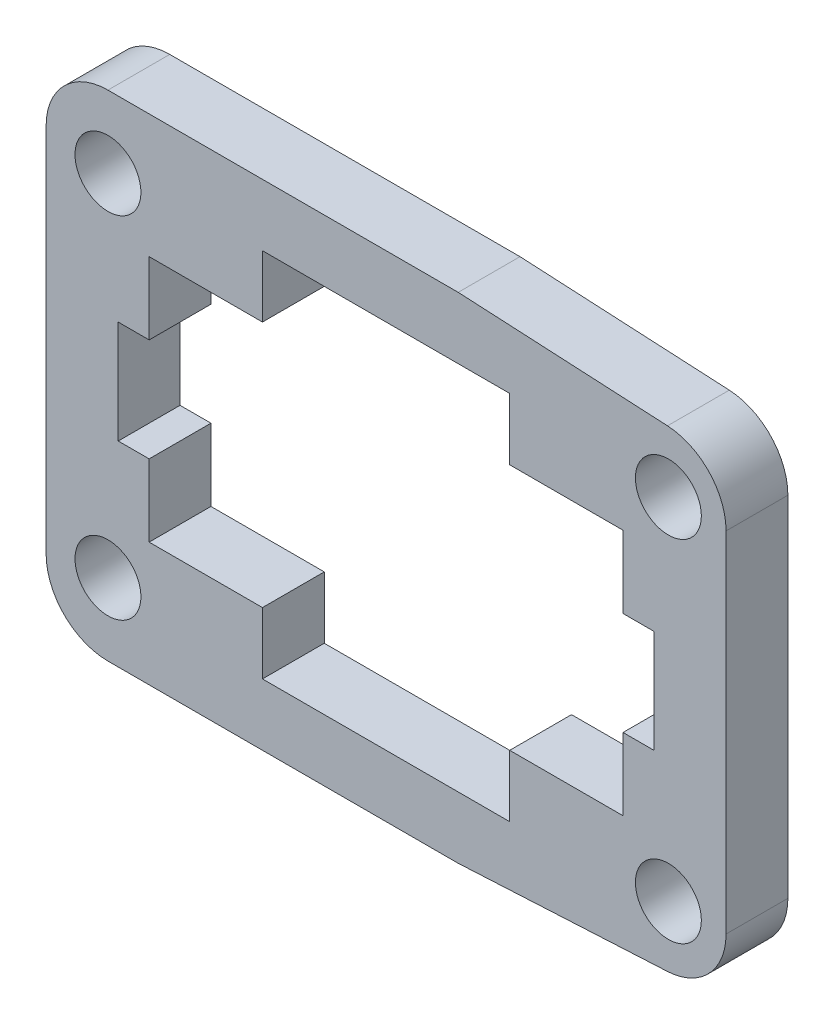
SolidWorks part; units mm, degrees
ref_plane "前视基准面" through (0, 0, 0) normal (0, 0, 1) x (1, 0, 0)
ref_plane "上视基准面" through (0, 0, 0) normal (0, 1, 0) x (1, 0, 0)
ref_plane "右视基准面" through (0, 0, 0) normal (1, 0, 0) x (0, 0, -1)
ref_plane "基准面4" through (0, 0, 3) normal (0, 0, 1) x (1, 0, 0)
sketch "草图1" plane through (0, 0, 3) normal (0, 0, 1) x (1, 0, 0)
  line L0 (13.8437, 23.9998) -> (-3.1571, 23.9998)
  line L1 (-6.1571, 20.9998) -> (-6.1571, 3)
  line L2 (-3.1571, 0) -> (13.8437, 0)
  line L3 (13.8437, 0) -> (24.0014, 0.533)
  line L4 (26.8442, 3.5289) -> (26.8442, 20.4719)
  line L5 (24.0011, 23.4678) -> (13.8437, 23.9998)
  line L6 (21.8432, 14.4995) -> (23.3435, 14.4995)
  line L7 (23.3435, 14.4995) -> (23.3435, 9.5)
  line L8 (23.3435, 9.5) -> (21.8432, 9.5)
  line L9 (21.8432, 9.5) -> (21.8432, 6)
  line L10 (21.8432, 6) -> (16.3434, 6)
  line L11 (16.3434, 6) -> (16.3434, 3)
  line L12 (16.3434, 3) -> (4.3434, 3)
  line L13 (4.3434, 3) -> (4.3434, 6)
  line L14 (4.3434, 6) -> (-1.1565, 6)
  line L15 (-1.1565, 6) -> (-1.1565, 9.5)
  line L16 (-1.1565, 9.5) -> (-2.6568, 9.5)
  line L17 (-2.6568, 9.5) -> (-2.6568, 14.4995)
  line L18 (-2.6568, 14.4995) -> (-1.1565, 14.4995)
  line L19 (-1.1565, 14.4995) -> (-1.1565, 17.9998)
  line L20 (-1.1565, 17.9998) -> (4.3434, 17.9998)
  line L21 (4.3434, 17.9998) -> (4.3434, 20.9998)
  line L22 (4.3434, 20.9998) -> (16.3434, 20.9998)
  line L23 (16.3434, 20.9998) -> (16.3434, 17.9998)
  line L24 (16.3434, 17.9998) -> (21.8432, 17.9998)
  line L25 (21.8432, 17.9998) -> (21.8432, 14.4995)
  arc A0 (-3.1571, 23.9998) -> (-6.1571, 20.9998) centre (-3.1571, 20.9998) ccw
  arc A1 (-6.1571, 3) -> (-3.1571, 0) centre (-3.1571, 3) ccw
  arc A2 (24.0014, 0.533) -> (26.8442, 3.5289) centre (23.8442, 3.5289) ccw
  arc A3 (26.8442, 20.4719) -> (24.0011, 23.4678) centre (23.8442, 20.4719) ccw
  circle A4 centre (24.044, 3.5011) radius 1.35
  circle A5 centre (-3.156, 3.5011) radius 1.35
  circle A6 centre (24.044, 20.4984) radius 1.35
  circle A7 centre (-3.156, 20.4984) radius 1
  point P42 (0, 0)
extrude "凸台-拉伸1" add sketch "草图1" against normal blind 3
sketch "草图2" plane through (0, 0, 3) normal (0, 0, 1) x (1, 0, 0)
  circle A0 centre (-3.156, 20.4984) radius 1.6
  circle A1 centre (24.044, 20.4984) radius 1.6
  circle A2 centre (24.044, 3.5011) radius 1.6
  circle A3 centre (-3.156, 3.5011) radius 1.6
  dimension "D1" = 3.2
extrude "切除-拉伸1" cut sketch "草图2" against normal through all
